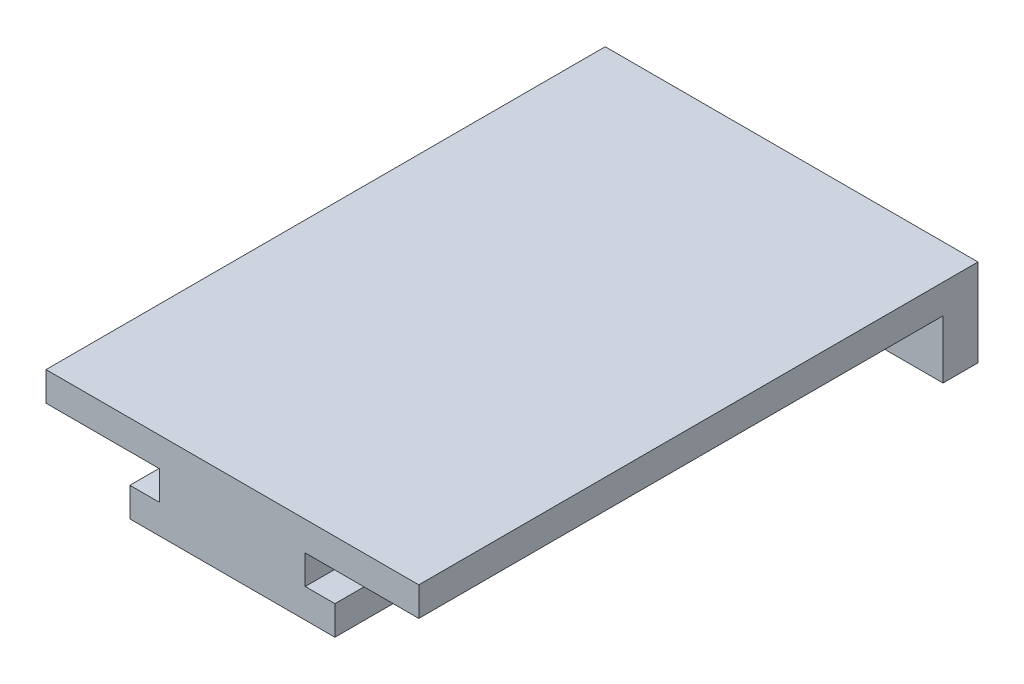
SolidWorks part; units mm, degrees
ref_plane "Front Plane" through (0, 0, 0) normal (0, 0, 1) x (1, 0, 0)
ref_plane "Top Plane" through (0, 0, 0) normal (0, 1, 0) x (1, 0, 0)
ref_plane "Right Plane" through (0, 0, 0) normal (1, 0, 0) x (0, 0, -1)
sketch "Sketch1" plane through (0, 0, 0) normal (0, 0, 1) x (1, 0, 0)
  line L1 (-3.2029, -2.2101) -> (5.5971, -2.2101)
  line L2 (-3.2029, -2.2101) -> (-3.2029, -4.7101)
  line L3 (-3.2029, -4.7101) -> (5.5971, -4.7101)
  line L4 (5.5971, -2.2101) -> (5.5971, -4.7101)
  line L5 (-3.2029, 0.2899) -> (3.0471, 0.2899)
  line L6 (-3.2029, 0.2899) -> (-3.2029, -2.2101)
  line L7 (-3.2029, -2.2101) -> (3.0471, -2.2101)
  line L8 (3.0471, 0.2899) -> (3.0471, -2.2101)
  line L13 (-3.2029, 0.2899) -> (12.7971, 0.2899)
  line L14 (-3.2029, 0.2899) -> (-3.2029, 2.7899)
  line L15 (-3.2029, 2.7899) -> (12.7971, 2.7899)
  line L16 (12.7971, 0.2899) -> (12.7971, 2.7899)
  dimension "D1" = 2.5
  dimension "D2" = 2.5
  dimension "D3" = 2.5
  dimension "D4" = 8.8
  dimension "D5" = 6.25
  dimension "D6" = 16
extrude "Boss-Extrude1" add sketch "Sketch1" along normal blind 45 contours L13 L16 L15 L14 L5 | L8 L5 L6 L1 | L4 L1 L2 L3
sketch "Sketch2" plane through (12.7971, 0, 0) normal (1, 0, 0) x (0, 0, -1)
  line L1 (-45, -4.7101) -> (-36.3578, -4.7101)
  line L2 (-45, -4.7101) -> (-45, -7.7101)
  line L3 (-45, -7.7101) -> (-36.3578, -7.7101)
  line L4 (-36.3578, -4.7101) -> (-36.3578, -7.7101)
  line L5 (-45, -7.7101) -> (-43, -7.7101)
  line L6 (-45, -7.7101) -> (-45, -14.7101)
  line L7 (-45, -14.7101) -> (-43, -14.7101)
  line L8 (-43, -7.7101) -> (-43, -14.7101)
  dimension "D1" = 3
  dimension "D2" = 7
  dimension "D3" = 2
mirror "Mirror1" about plane through (-3.2029, 0, 45) normal (-1, 0, 0) of "Boss-Extrude1"
sketch "Sketch8" plane through (0, -4.7101, 0) normal (0, -1, 0) x (1, 0, 0)
  line L0 (-3.2029, 45) -> (-3.2029, -0.3624) construction
  line L1 (-12.0029, 45) -> (5.5971, 45) construction
  line L2 (-19.2029, 45) -> (-19.2029, 0) construction
  line L3 (-19.2029, 22.5) -> (12.7971, 22.5) construction
  line L4 (12.7971, 45) -> (12.7971, 0) construction
  circle A0 centre (-3.2029, 32.5) radius 1.5
  circle A1 centre (-3.2029, 12.5) radius 1.5
  dimension "D1" = 10
extrude "Cut-Extrude2" cut sketch "Sketch8" against normal blind 3 draft 45
sketch "Sketch9" plane through (0, 0, 0) normal (0, 0, -1) x (-1, 0, 0)
  line L0 (12.0029, -4.7101) -> (-5.5971, -4.7101) construction
  line L1 (-12.7971, 2.7899) -> (19.2029, 2.7899)
  line L2 (-12.7971, 2.7899) -> (-12.7971, -4.7101)
  line L3 (-12.7971, -4.7101) -> (19.2029, -4.7101)
  line L4 (19.2029, 2.7899) -> (19.2029, -4.7101)
  point P5 (19.2029, 2.7899)
extrude "Boss-Extrude3" add sketch "Sketch9" along normal blind 3
